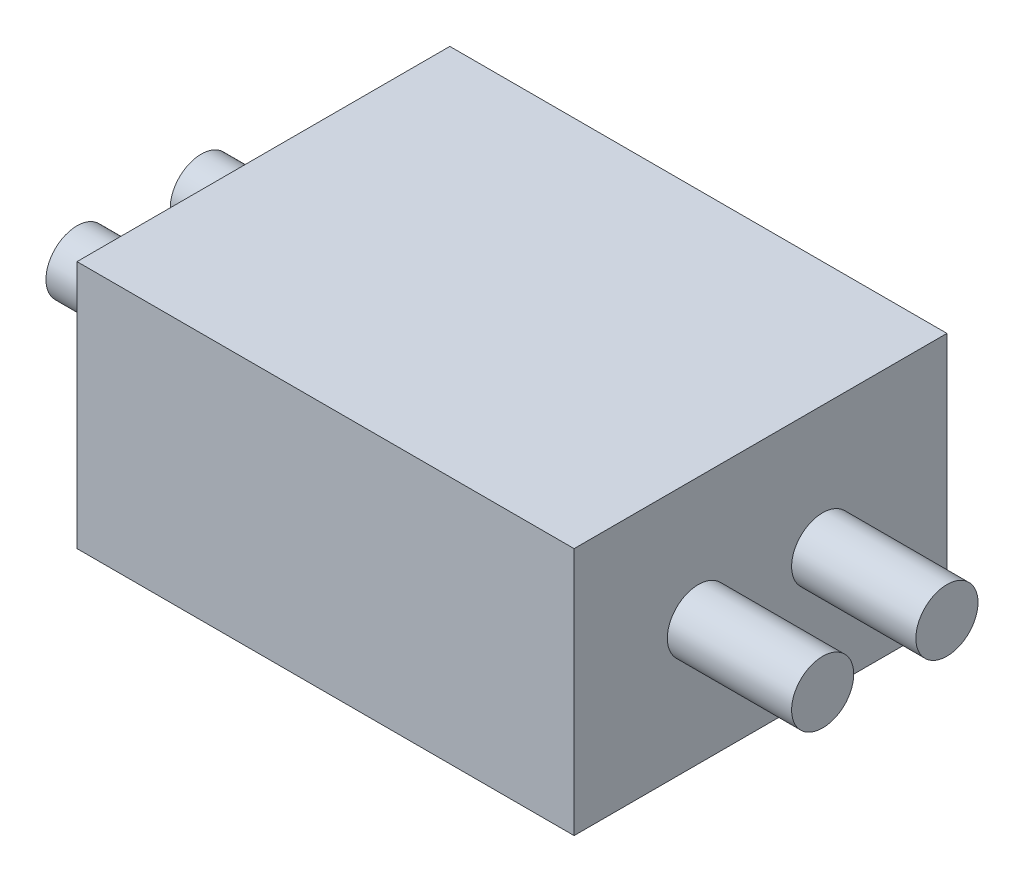
SolidWorks part; units mm, degrees
ref_plane "Front Plane" through (0, 0, 0) normal (0, 0, 1) x (1, 0, 0)
ref_plane "Top Plane" through (0, 0, 0) normal (0, 1, 0) x (1, 0, 0)
ref_plane "Right Plane" through (0, 0, 0) normal (1, 0, 0) x (0, 0, -1)
sketch "Sketch1" plane through (0, 0, 0) normal (0, 1, 0) x (1, 0, 0)
  line L1 (-4, -3) -> (4, -3)
  line L2 (-4, -3) -> (-4, 3)
  line L3 (-4, 3) -> (4, 3)
  line L4 (4, -3) -> (4, 3)
  line L5 (-4, -3) -> (4, 3) construction
  line L6 (-4, 3) -> (4, -3) construction
  point P0 (0, 0)
  dimension "D1" = 8
  dimension "D2" = 6
extrude "Boss-Extrude1" add sketch "Sketch1" along normal blind 4
sketch "Sketch2" plane through (0, 0, 0) normal (1, 0, 0) x (0, 0, -1)
  line L0 (-1, 2) -> (1, 2) construction
  line L1 (-3, 4) -> (-3, 0) construction
  circle A0 centre (-1, 2) radius 0.5
  circle A1 centre (1, 2) radius 0.5
  point P3 (0, 2)
  point P5 (0, 0)
  point P7 (-3, 2)
  dimension "D2" = 1
  dimension "D3" = 1
  dimension "D1" = 2
extrude "Boss-Extrude2" add sketch "Sketch2" along normal mid plane 12
